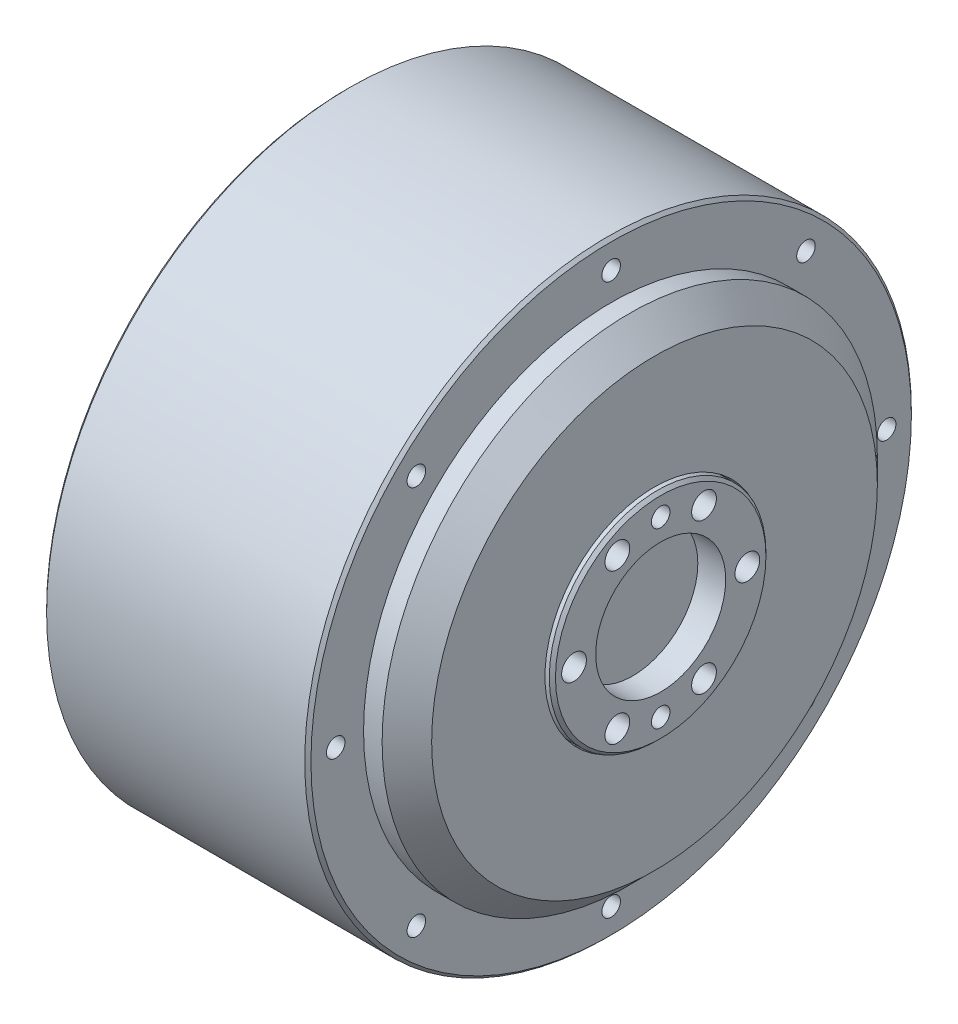
SolidWorks part; units mm, degrees
material "Magnesium Alloy"
ref_plane "Front Plane" through (0, 0, 0) normal (0, 0, 1) x (1, 0, 0)
ref_plane "Top Plane" through (0, 0, 0) normal (0, 1, 0) x (1, 0, 0)
ref_plane "Right Plane" through (0, 0, 0) normal (1, 0, 0) x (0, 0, -1)
sketch "Sketch1" plane through (0, 0, 0) normal (0, 0, 1) x (1, 0, 0)
  line L0 (-50.7, 49) -> (-50.7, 0)
  line L1 (-50.7, 0) -> (-8, 0)
  line L2 (-8, 0) -> (-8, 49)
  line L3 (-8, 49) -> (-50.7, 49)
  line L4 (-50.7, 0) -> (-8, 0) construction
revolve "Revolve1" add sketch "Sketch1" angle 360 about L4
sketch "Sketch2" plane through (-50.7, 0, 0) normal (-1, 0, 0) x (0, 0, 1)
  circle A0 centre (0, 0) radius 35.5
extrude "Boss-Extrude1" add sketch "Sketch2" along normal blind 11.2
sketch "Sketch3" plane through (-61.9, 0, 0) normal (-1, 0, 0) x (0, 0, 1)
  line L0 (5.253, 35.1092) -> (32.5533, 14.161)
  arc A0 (32.5533, 14.161) -> (5.253, 35.1092) centre (0, 0) ccw
extrude "Cut-Extrude1" cut sketch "Sketch3" against normal blind 8
sketch "Sketch4" plane through (-8, 0, 0) normal (1, 0, 0) x (0, 0, -1)
  circle A0 centre (0, 0) radius 40
extrude "Boss-Extrude2" add sketch "Sketch4" along normal blind 3
sketch "Sketch5" plane through (-5, 0, 0) normal (1, 0, 0) x (0, 0, -1)
  circle A0 centre (0, 0) radius 40
extrude "Boss-Extrude3" add sketch "Sketch5" along normal blind 4 draft 45
hole_wizard "M33 Clearance Hole1" positions "Sketch7" profile "Sketch6" hole size "M33" standard "ANSI Metric"
sketch "Sketch7" plane through (-1, 0, 0) normal (1, 0, 0) x (0, 0, -1)
  point P0 (0, 0)
sketch "Sketch6" plane through (-1, 0, 0) normal (0, 1, 0) x (0, 0, -1)
  line L0 (0, 0) -> (0, 7.5)
  line L1 (0, 7.5) -> (17.7, 7.5)
  line L2 (17.7, 7.5) -> (17.7, 0)
  line L5 (17.7, 0) -> (0, 0)
  line L10 (0, 7.5) -> (-17.7, 7.5) construction
  line L11 (0, -6.35) -> (0, 107.95) construction
  dimension "Hole Dia." = 35.4
  dimension "Hole Depth" = 7.5
  dimension "Drill Angle" = 180
sketch "Sketch8" plane through (0, 0, 0) normal (0, 0, 1) x (1, 0, 0)
  line L0 (-8.5, 17.5) -> (-8.5, 0)
  line L1 (-8.5, 0) -> (0, 0)
  line L2 (0, 0) -> (0, 17.5)
  line L3 (0, 17.5) -> (-8.5, 17.5)
  line L4 (-8.5, 0) -> (0, 0) construction
revolve "Revolve2" add sketch "Sketch8" angle 360 about L4
hole_wizard "Ø3.0 (3) Diameter Hole1" positions "Sketch10" profile "Sketch9" hole size "Ø3.0" standard "ANSI Metric"
sketch "Sketch10" plane through (-50.7, 0, 0) normal (-1, 0, 0) x (0, 0, 1)
  point P0 (39.2649, 16.264)
  point P1 (39.2649, -16.264)
  point P2 (16.264, -39.2649)
  point P3 (-16.264, -39.2649)
  point P4 (-39.2649, -16.264)
  point P5 (-39.2649, 16.264)
  point P6 (-16.264, 39.2649)
  point P7 (16.264, 39.2649)
sketch "Sketch9" plane through (-50.7, 16.264, 39.2649) normal (0, 1, 0) x (0, 0, 1)
  line L0 (0, 0) -> (0, 4)
  line L1 (0, 4) -> (1.5, 4)
  line L2 (1.5, 4) -> (1.5, 0)
  line L5 (1.5, 0) -> (0, 0)
  line L10 (0, 4) -> (-1.5, 4) construction
  line L11 (0, -6.35) -> (0, 107.95) construction
  dimension "Hole Dia." = 3
  dimension "Hole Depth" = 4
  dimension "Drill Angle" = 180
hole_wizard "Ø3.0 (3) Diameter Hole2" positions "Sketch12" profile "Sketch11" hole size "Ø3.0" standard "ANSI Metric"
sketch "Sketch12" plane through (-8, 0, 0) normal (1, 0, 0) x (0, 0, -1)
  point P0 (31.4663, 31.4663)
  point P1 (44.5, 0)
  point P2 (31.4663, -31.4663)
  point P3 (0, -44.5)
  point P4 (-31.4663, -31.4663)
  point P5 (-44.5, 0)
  point P6 (-31.4663, 31.4663)
  point P7 (0, 44.5)
sketch "Sketch11" plane through (-8, 31.4663, -31.4663) normal (0, 1, 0) x (0, 0, -1)
  line L0 (0, 0) -> (0, 8)
  line L1 (0, 8) -> (1.5, 8)
  line L2 (1.5, 8) -> (1.5, 0)
  line L5 (1.5, 0) -> (0, 0)
  line L10 (0, 8) -> (-1.5, 8) construction
  line L11 (0, -6.35) -> (0, 107.95) construction
  dimension "Hole Dia." = 3
  dimension "Hole Depth" = 8
  dimension "Drill Angle" = 180
hole_wizard "Ø21.0 (21) Diameter Hole1" positions "Sketch14" profile "Sketch13" hole size "Ø21.0" standard "ANSI Metric"
sketch "Sketch14" plane through (0, 0, 0) normal (1, 0, 0) x (0, 0, -1)
  point P0 (0, 0)
sketch "Sketch13" plane through (0, 0, 0) normal (0, 1, 0) x (0, 0, -1)
  line L0 (0, 0) -> (0, 4.5)
  line L1 (0, 4.5) -> (10.5, 4.5)
  line L2 (10.5, 4.5) -> (10.5, 0)
  line L5 (10.5, 0) -> (0, 0)
  line L10 (0, 4.5) -> (-10.5, 4.5) construction
  line L11 (0, -6.35) -> (0, 107.95) construction
  dimension "Hole Dia." = 21
  dimension "Hole Depth" = 4.5
  dimension "Drill Angle" = 180
hole_wizard "Ø4.0 (4) Diameter Hole1" positions "Sketch16" profile "Sketch15" hole size "Ø4.0" standard "ANSI Metric"
sketch "Sketch16" plane through (0, 0, 0) normal (1, 0, 0) x (0, 0, -1)
  point P0 (-14, 0)
  point P1 (-7, 12.1244)
  point P2 (7, 12.1244)
  point P3 (14, 0)
  point P4 (7, -12.1244)
  point P5 (-7, -12.1244)
sketch "Sketch15" plane through (0, 0, 14) normal (0, 1, 0) x (0, 0, -1)
  line L0 (0, 0) -> (0, 8)
  line L1 (0, 8) -> (2, 8)
  line L2 (2, 8) -> (2, 0)
  line L5 (2, 0) -> (0, 0)
  line L10 (0, 8) -> (-2, 8) construction
  line L11 (0, -6.35) -> (0, 107.95) construction
  dimension "Hole Dia." = 4
  dimension "Hole Depth" = 8
  dimension "Drill Angle" = 180
hole_wizard "Ø3.0 (3) Diameter Hole3" positions "Sketch18" profile "Sketch17" hole size "Ø3.0" standard "ANSI Metric"
sketch "Sketch18" plane through (0, 0, 0) normal (1, 0, 0) x (0, 0, -1)
  point P0 (0, -14)
  point P1 (0, 14)
sketch "Sketch17" plane through (0, -14, 0) normal (0, 1, 0) x (0, 0, -1)
  line L0 (0, 0) -> (0, 3)
  line L1 (0, 3) -> (1.5, 3)
  line L2 (1.5, 3) -> (1.5, 0)
  line L5 (1.5, 0) -> (0, 0)
  line L10 (0, 3) -> (-1.5, 3) construction
  line L11 (0, -6.35) -> (0, 107.95) construction
  dimension "Hole Dia." = 3
  dimension "Hole Depth" = 3
  dimension "Drill Angle" = 180
chamfer "Chamfer1" distance 0.5 angle 45 3 edges at (-50.7, 0, -49) (0, 0, -17.5) (-8, 0, -49)
sketch "Sketch19" plane through (-61.9, 0, 0) normal (-1, 0, 0) x (0, 0, 1)
  circle A0 centre (0, 0) radius 38.4401
extrude "Cut-Extrude2" cut sketch "Sketch19" against normal offset from surface (10.2 mm away) 1 up to face at (-50.7, 0, 48.5)
sketch "Sketch20" plane through (-51.7, 0, 0) normal (-1, 0, 0) x (0, 0, 1)
  circle A0 centre (0, 0) radius 32.5
  circle A1 centre (0, 0) radius 34
  circle A2 centre (0, 0) radius 38.368
  circle M2 centre (0, 0) radius 35.5
  dimension "D1" = 65
  dimension "D2" = 68
extrude "Cut-Extrude3" cut sketch "Sketch20" against normal up to surface (1 mm away) contours A1 M2 | A2 M2 | A0 up to face at (-50.7, 0, 48.5)
sketch "Sketch21" plane through (-50.7, 0, 0) normal (-1, 0, 0) x (0, 0, 1)
  line L0 (-16.264, 39.2649) -> (16.264, -39.2649) construction
  circle A0 centre (0, 0) radius 27.5 construction
  point P3 (-10.5238, 25.4067)
  point P7 (27.2647, -3.5895)
  point P8 (-16.7409, -21.8172)
  point P9 (0, 0)
  dimension "D1" = 55
  dimension "D3" = 0
  dimension "D2" = 3
hole_wizard "Tap Drill for M3 Tap2" positions "Sketch21" profile "Sketch23" hole size "M3" standard "DIN"
sketch "Sketch23" plane through (-50.7, -21.8172, -16.7409) normal (0, 1, 0) x (0, 0, 1)
  line L0 (0, 0) -> (0, 2.7511)
  line L1 (0, 2.7511) -> (1.25, 2)
  line L2 (1.25, 2) -> (1.25, 0.025)
  line L3 (1.25, 0.025) -> (1.275, 0)
  line L5 (1.275, 0) -> (0, 0)
  line L6 (-1.25, 0.025) -> (-1.275, 0) construction
  line L10 (0, 2.7511) -> (-1.25, 2) construction
  line L11 (0, -6.35) -> (0, 107.95) construction
  dimension "Hole Dia." = 2.5
  dimension "Hole Depth" = 2
  dimension "Near C'Sink Dia." = 2.55
  dimension "Near C'Sink Angle" = 90
  dimension "Drill Angle" = 118
sketch "Sketch24" plane through (-50.7, 0, 0) normal (-1, 0, 0) x (0, 0, 1)
  circle A0 centre (-10.5238, 25.4067) radius 2.55
  circle A1 centre (-16.7409, -21.8172) radius 2.55
  circle A2 centre (27.2647, -3.5895) radius 2.55
  circle A3 centre (-10.5238, 25.4067) radius 1.25 construction
  circle A4 centre (27.2647, -3.5895) radius 1.25 construction
  circle A5 centre (-16.7409, -21.8172) radius 1.25 construction
  circle A6 centre (-10.5238, 25.4067) radius 1.25
  circle A7 centre (27.2647, -3.5895) radius 1.25
  circle A8 centre (-16.7409, -21.8172) radius 1.25
  dimension "D1" = 5.1
extrude "Boss-Extrude4" add sketch "Sketch24" along normal blind 3
